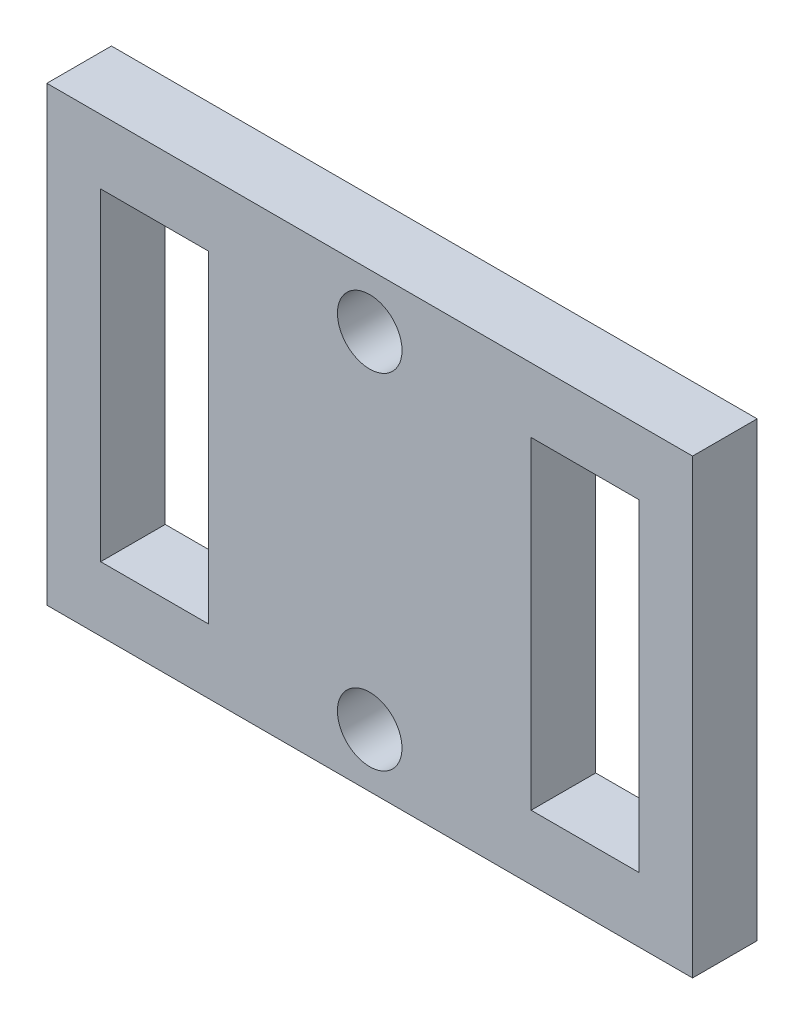
SolidWorks part; units mm, degrees
material "Thornel Mat VMA"
ref_plane "前视基准面" through (0, 0, 0) normal (0, 0, 1) x (1, 0, 0)
ref_plane "上视基准面" through (0, 0, 0) normal (0, 1, 0) x (1, 0, 0)
ref_plane "右视基准面" through (0, 0, 0) normal (1, 0, 0) x (0, 0, -1)
sketch "草图1" plane through (0, 0, 0) normal (0, 0, 1) x (1, 0, 0)
  line L0 (-15, 0) -> (15, 0) construction
  line L1 (-15, 10.5) -> (15, 10.5)
  line L2 (-15, 10.5) -> (-15, -10.5)
  line L3 (-15, -10.5) -> (15, -10.5)
  line L4 (15, 10.5) -> (15, -10.5)
  line L5 (-15, 10.5) -> (15, -10.5) construction
  line L6 (-15, -10.5) -> (15, 10.5) construction
  circle A0 centre (0, 8) radius 1.5
  circle A1 centre (0, -8) radius 1.5
  point P0 (0, 0)
  dimension "D3" = 8
  dimension "D4" = 3
  dimension "D1" = 21
  dimension "D2" = 30
extrude "凸台-拉伸1" add sketch "草图1" along normal blind 3
sketch "草图2" plane through (0, 0, 3) normal (0, 0, 1) x (1, 0, 0)
  line L0 (0, 10.5) -> (0, -10.5) construction
  line L1 (15, 10.5) -> (-15, 10.5) construction
  line L2 (-15, -10.5) -> (15, -10.5) construction
  line L3 (12.5, -7.5) -> (7.5, 7.5) construction
  line L4 (-12.5, 7.5) -> (-7.5, 7.5)
  line L5 (-12.5, 7.5) -> (-12.5, -7.5)
  line L6 (-12.5, -7.5) -> (-7.5, -7.5)
  line L7 (-7.5, 7.5) -> (-7.5, -7.5)
  line L8 (-12.5, 7.5) -> (-7.5, -7.5) construction
  line L9 (-12.5, -7.5) -> (-7.5, 7.5) construction
  line L10 (12.5, 7.5) -> (7.5, -7.5) construction
  line L11 (7.5, 7.5) -> (7.5, -7.5)
  line L12 (12.5, -7.5) -> (7.5, -7.5)
  line L13 (12.5, 7.5) -> (12.5, -7.5)
  line L14 (12.5, 7.5) -> (7.5, 7.5)
  point P6 (-10, 0)
  point P11 (0, 0)
  point P17 (10, 0)
  dimension "D1" = 15
  dimension "D2" = 5
  dimension "D3" = 7.5
extrude "切除-拉伸1" cut sketch "草图2" against normal through all
